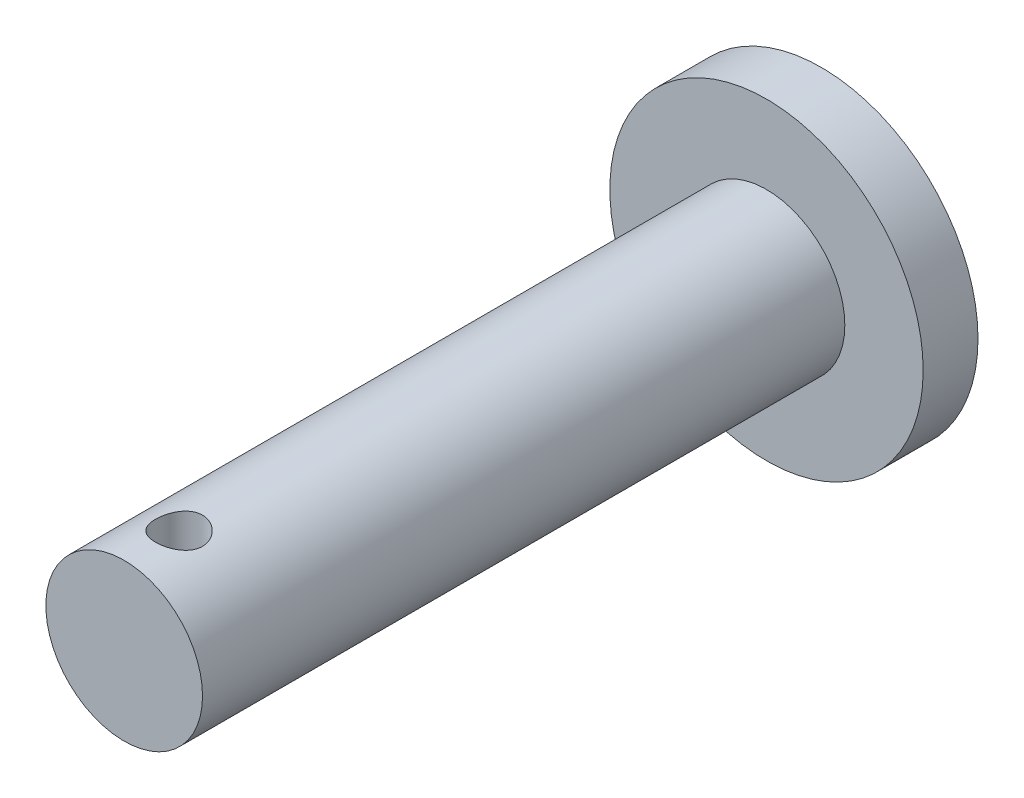
SolidWorks part; units mm, degrees
ref_plane "Ön Düzlem" through (0, 0, 0) normal (0, 0, 1) x (1, 0, 0)
ref_plane "Üst Düzlem" through (0, 0, 0) normal (0, 1, 0) x (1, 0, 0)
ref_plane "Sağ Düzlem" through (0, 0, 0) normal (1, 0, 0) x (0, 0, -1)
sketch "Çizim1" plane through (0, 0, 0) normal (0, 0, 1) x (1, 0, 0)
  circle A0 centre (0, 0) radius 20
  dimension "D1" = 40
extrude "Yükseklik-Ekstrüzyon1" add sketch "Çizim1" along normal blind 7
sketch "Çizim2" plane through (0, 0, 7) normal (0, 0, 1) x (1, 0, 0)
  circle A0 centre (0, 0) radius 10
  dimension "D1" = 20
extrude "Yükseklik-Ekstrüzyon2" add sketch "Çizim2" along normal blind 82
sketch "Çizim3" plane through (0, 0, 0) normal (0, 1, 0) x (1, 0, 0)
  line L0 (0, -93.0602) -> (0, 1.7294) construction
  line L1 (-10, -89) -> (10, -89) construction
  circle A0 centre (0, -82) radius 3
  dimension "D1" = 6
  dimension "D2" = 7
extrude "Kes-Ekstrüzyon1" cut sketch "Çizim3" against normal mid plane 82
